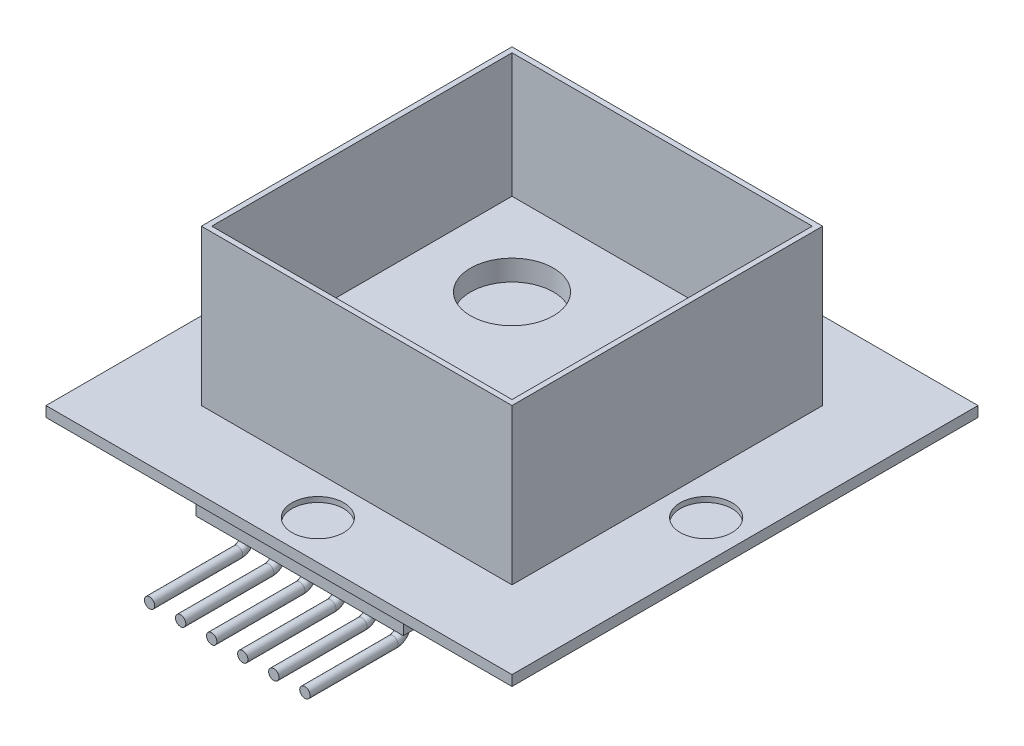
SolidWorks part; units mm, degrees
ref_plane "Front Plane" through (0, 0, 0) normal (0, 0, 1) x (1, 0, 0)
ref_plane "Top Plane" through (0, 0, 0) normal (0, 1, 0) x (1, 0, 0)
ref_plane "Right Plane" through (0, 0, 0) normal (1, 0, 0) x (0, 0, -1)
sketch "Sketch1" plane through (0, 0, 0) normal (0, 1, 0) x (1, 0, 0)
  line L1 (0, 0) -> (45, 0)
  line L2 (0, 0) -> (0, 45)
  line L3 (0, 45) -> (45, 45)
  line L4 (45, 0) -> (45, 45)
  dimension "D1" = 45
  dimension "D2" = 45
extrude "Boss-Extrude1" add sketch "Sketch1" along normal blind 1
sketch "Sketch2" plane through (0, 1, 0) normal (0, 1, 0) x (1, 0, 0)
  line L0 (7.5, 37.5) -> (7.5, 7.5)
  line L1 (7.5, 7.5) -> (37.5, 7.5)
  line L2 (37.5, 7.5) -> (37.5, 37.5)
  line L3 (37.5, 37.5) -> (7.5, 37.5)
  line L4 (45, 45) -> (0, 45) construction
  line L5 (8, 37) -> (37, 37)
  line L6 (8, 37) -> (8, 8)
  line L7 (8, 8) -> (37, 8)
  line L8 (37, 37) -> (37, 8)
  line L9 (0, 45) -> (0, 0) construction
  dimension "D1" = 30
  dimension "D2" = 29
  dimension "D3" = 30
  dimension "D4" = 29
  dimension "D5" = 7.5
  dimension "D6" = 8
  dimension "D7" = 7.5
  dimension "D8" = 8
extrude "Boss-Extrude2" add sketch "Sketch2" along normal blind 15
sketch "Sketch3" plane through (0, 1, 0) normal (0, 1, 0) x (1, 0, 0)
  line L8 (37, 37) -> (8, 37)
  line L9 (8, 37) -> (8, 8)
  line L10 (8, 8) -> (37, 8)
  line L11 (37, 8) -> (37, 37)
  line L12 (37, 37) -> (8, 37)
  line L13 (8, 37) -> (8, 8)
  line L14 (8, 8) -> (37, 8)
  line L15 (37, 8) -> (37, 37)
  dimension "D1" = 0
extrude "Boss-Extrude3" add sketch "Sketch3" along normal blind 3
sketch "Sketch4" plane through (0, 4, 0) normal (0, 1, 0) x (1, 0, 0)
  line L0 (0, 45) -> (0, 0) construction
  line L1 (45, 0) -> (45, 45) construction
  line L2 (45, 45) -> (0, 45) construction
  line L3 (0, 0) -> (45, 0) construction
  circle A0 centre (16, 29) radius 4
  circle A1 centre (29, 29) radius 4
  circle A2 centre (29, 16) radius 4
  circle A3 centre (16, 16) radius 4
  point P14 (0, 0)
  point P15 (0, 0)
  point P16 (0, 0)
  point P17 (0, 0)
  dimension "D1" = 8
  dimension "D2" = 8
  dimension "D3" = 8
  dimension "D4" = 8
  dimension "D5" = 16
  dimension "D6" = 16
  dimension "D7" = 16
  dimension "D8" = 16
extrude "Cut-Extrude1" cut sketch "Sketch4" against normal blind 2
sketch "Sketch5" plane through (0, 1, 0) normal (0, 1, 0) x (1, 0, 0)
  line L0 (0, 45) -> (0, 0) construction
  line L1 (45, 45) -> (0, 45) construction
  line L2 (45, 0) -> (45, 45) construction
  line L3 (0, 0) -> (45, 0) construction
  circle A0 centre (41.25, 22.5) radius 2.5
  circle A1 centre (22.5, 41.25) radius 2.5
  circle A2 centre (3.75, 22.5) radius 2.5
  circle A3 centre (22.5, 3.75) radius 2.5
  point P16 (0, 0)
  point P17 (0, 0)
  dimension "D1" = 5
  dimension "D2" = 5
  dimension "D3" = 5
  dimension "D4" = 5
  dimension "D5" = 3.75
  dimension "D6" = 3.75
  dimension "D7" = 3.75
  dimension "D8" = 3.75
  dimension "D9" = 22.5
  dimension "D10" = 22.5
extrude "Cut-Extrude2" cut sketch "Sketch5" against normal blind 0.5
sketch "Sketch7" plane through (0, 0, 0) normal (0, -1, 0) x (1, 0, 0)
  line L0 (0, -45) -> (0, 0) construction
  line L1 (12.5, -2) -> (32.5, -2)
  line L2 (12.5, -2) -> (12.5, -7)
  line L3 (12.5, -7) -> (32.5, -7)
  line L4 (32.5, -2) -> (32.5, -7)
  line L5 (0, 0) -> (45, 0) construction
  dimension "D1" = 20
  dimension "D2" = 5
  dimension "D3" = 12.5
  dimension "D4" = 2
extrude "Boss-Extrude4" add sketch "Sketch7" along normal blind 3
ref_plane "Plane1" through (15, 0, 0) normal (-1, 0, 0) x (0, 0, 1)
sketch "Sketch8" plane through (15, 0, 0) normal (-1, 0, 0) x (0, 0, 1)
  line L0 (-4.5, -3) -> (-4.5, -4.5)
  line L1 (-2, -3) -> (-7, -3) construction
  line L2 (-3.5, -5.5) -> (5, -5.5)
  arc A0 (-4.5, -4.5) -> (-3.5, -5.5) centre (-3.5, -4.5) ccw
  dimension "D2" = 1
  dimension "D1" = 1.5
  dimension "D3" = 8.5
ref_plane "Plane2" through (15, -5.5, 5) normal (0, 0, 1) x (1, 0, 0)
sketch "Sketch9" plane through (15, -5.5, 5) normal (0, 0, 1) x (1, 0, 0)
  line L0 (0, 1) -> (0, 0) construction
  line L1 (17.5, 2.5) -> (-2.5, 2.5) construction
  circle A0 centre (0, 0) radius 0.5
  dimension "D1" = 1
  dimension "D2" = 2.5
sweep "Sweep1" add profiles "Sketch9" path "Sketch8"
pattern_linear "LPattern1" count 6 spacing 3 along (1, 0, 0) of "Sweep1"
